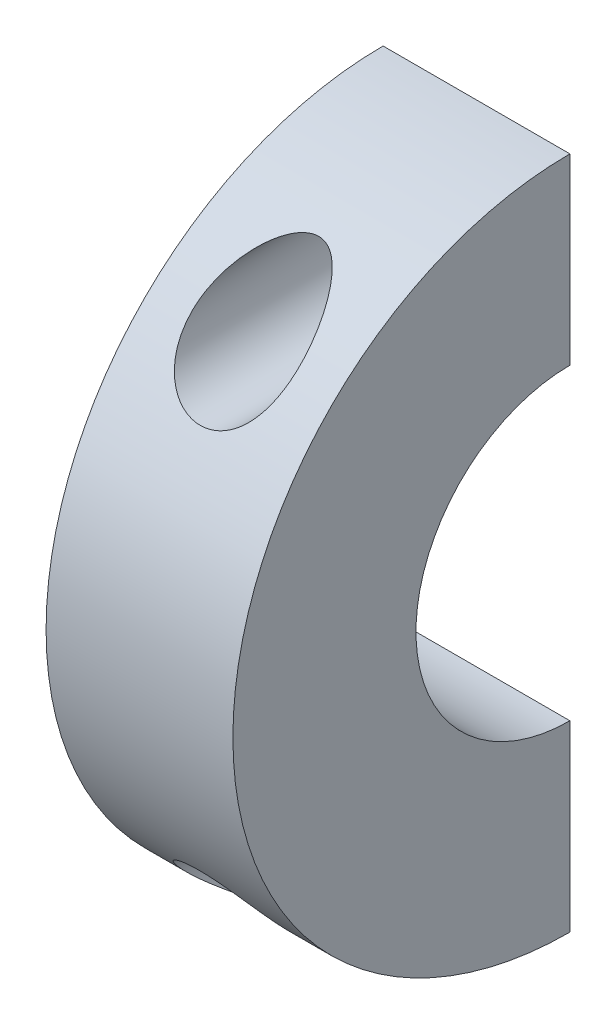
SolidWorks part; units mm, degrees
ref_plane "Front Plane" through (0, 0, 0) normal (0, 0, 1) x (1, 0, 0)
ref_plane "Top Plane" through (0, 0, 0) normal (0, 1, 0) x (1, 0, 0)
ref_plane "Right Plane" through (0, 0, 0) normal (1, 0, 0) x (0, 0, -1)
sketch "Sketch1" plane through (0, 0, 0) normal (0, 0, 1) x (1, 0, 0)
  line L0 (40.7642, 22.1) -> (36.125, 22.1)
  line L1 (53.3, 30.34) -> (9.2785, 30.34) construction
  line L2 (36.125, 22.1) -> (36.125, 12.3)
  line L16 (46.125, 22.1) -> (40.7642, 22.1)
  line L22 (36.125, 12.3) -> (46.125, 12.3)
  line L23 (46.125, 12.3) -> (46.125, 22.1)
  dimension "D1" = 8.24
  dimension "D2" = 10
  dimension "D3" = 9.8
revolve "Revolve1" add sketch "Sketch1" angle 180 about L1
sketch "Sketch2" plane through (0, 0, 0) normal (0, 0, -1) x (-1, 0, 0)
  line L0 (-40.9963, 30.3806) -> (-40.9963, 48.2697) construction
  line L3 (-36.125, 43.48) -> (-46.125, 43.48) construction
  line L5 (-35, 223.9966) -> (-45, 223.9966) construction
  line L8 (-61.9362, 30.3806) -> (-20.0565, 30.3806) construction
  line L9 (-36.125, 38.58) -> (-36.125, 48.38) construction
  line L10 (-46.125, 48.38) -> (-46.125, 38.58) construction
  circle A1 centre (-40, 223.9966) radius 2.8
  circle A3 centre (-41.125, 43.48) radius 2.8
  circle A4 centre (-41.125, 17.2813) radius 2.8
  point P23 (-40.9963, 30.3806)
  dimension "D1" = 5.6
  dimension "D2" = 13.1
extrude "Cut-Extrude1" cut sketch "Sketch2" against normal up to body
